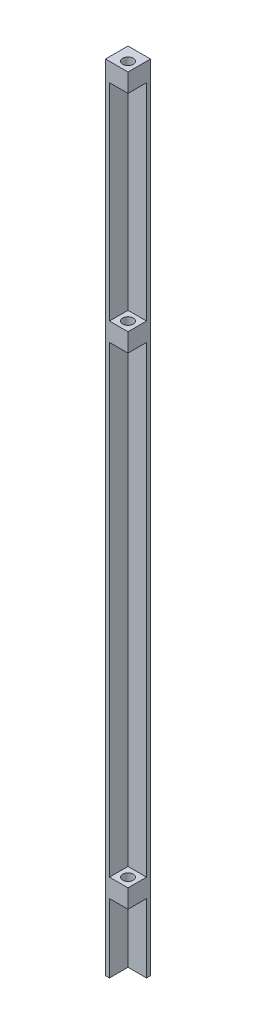
SolidWorks part; units mm, degrees
ref_plane "Front" through (0, 0, 0) normal (0, 0, 1) x (1, 0, 0)
ref_plane "Top" through (0, 0, 0) normal (0, 1, 0) x (1, 0, 0)
ref_plane "Right" through (0, 0, 0) normal (1, 0, 0) x (0, 0, -1)
sketch "Sketch1" plane through (0, 0, 0) normal (0, 1, 0) x (1, 0, 0)
  line L1 (0, 0) -> (8.5, 0)
  line L2 (0, 0) -> (0, 8.5)
  line L3 (0, 8.5) -> (8.5, 8.5)
  line L4 (8.5, 0) -> (8.5, 8.5)
  dimension "D1" = 8.5
  dimension "D2" = 8.5
extrude "Boss-Extrude1" add sketch "Sketch1" along normal blind 300
ref_plane "Plane1" through (0, 33, 0) normal (0, -1, 0) x (-1, 0, 0)
sketch "Sketch2" plane through (0, 33, 0) normal (0, -1, 0) x (-1, 0, 0)
  line L0 (0, 8.5) -> (0, 0) construction
  line L1 (-8.5, 0) -> (-1.5, 0)
  line L2 (-8.5, 0) -> (-8.5, 7)
  line L3 (-8.5, 7) -> (-1.5, 7)
  line L4 (-1.5, 0) -> (-1.5, 7)
  line L5 (-8.5, 8.5) -> (0, 8.5) construction
  dimension "D1" = 1.5
  dimension "D2" = 1.5
extrude "Cut-Extrude2" cut sketch "Sketch2" against normal blind 175
sketch "Sketch4" plane through (0, 208, 0) normal (0, -1, 0) x (1, 0, 0)
  line L0 (8.5, 0) -> (1.5, 0) construction
  line L1 (8.5, -7) -> (8.5, 0) construction
  circle A0 centre (5, -3.5) radius 2
  point P0 (5, 0)
  point P1 (8.5, -3.5)
  dimension "D1" = 4
extrude "Cut-Extrude4" cut sketch "Sketch4" against normal blind 10
sketch "Sketch6" plane through (0, 0, 0) normal (0, -1, 0) x (1, 0, 0)
  line L0 (0, -8.5) -> (0, 0) construction
  line L1 (8.5, 0) -> (1.5, 0)
  line L2 (8.5, 0) -> (8.5, -7)
  line L3 (8.5, -7) -> (1.5, -7)
  line L4 (1.5, 0) -> (1.5, -7)
  line L5 (8.5, -8.5) -> (0, -8.5) construction
  dimension "D1" = 1.5
  dimension "D2" = 1.5
extrude "Cut-Extrude5" cut sketch "Sketch6" against normal blind 26
sketch "Sketch7" plane through (0, 26, 0) normal (0, -1, 0) x (1, 0, 0)
  line L0 (8.5, 0) -> (1.5, 0) construction
  line L1 (8.5, -7) -> (8.5, 0) construction
  circle A0 centre (5, -3.5) radius 2
  point P0 (5, 0)
  point P1 (8.5, -3.5)
  point P4 (5, -3.5)
  dimension "D1" = 4
extrude "Cut-Extrude6" cut sketch "Sketch7" against normal blind 26
sketch "Sketch8" plane through (0, 300, 0) normal (0, 1, 0) x (1, 0, 0)
  line L1 (8.5, 0) -> (1.5, 0)
  line L2 (8.5, 0) -> (8.5, 7)
  line L3 (8.5, 7) -> (1.5, 7)
  line L4 (1.5, 0) -> (1.5, 7)
  point P5 (1.5, 3.5)
  point P7 (5, 7)
  dimension "D1" = 7
  dimension "D2" = 7
extrude "Cut-Extrude7" cut sketch "Sketch8" against normal blind 85
sketch "Sketch9" plane through (0, 300, 0) normal (0, 1, 0) x (1, 0, 0)
  line L1 (1.5, 7) -> (8.5, 7)
  line L2 (1.5, 7) -> (1.5, 0)
  line L3 (1.5, 0) -> (8.5, 0)
  line L4 (8.5, 7) -> (8.5, 0)
  circle A0 centre (5, 3.5) radius 2
extrude "Boss-Extrude2" add sketch "Sketch9" against normal blind 7
